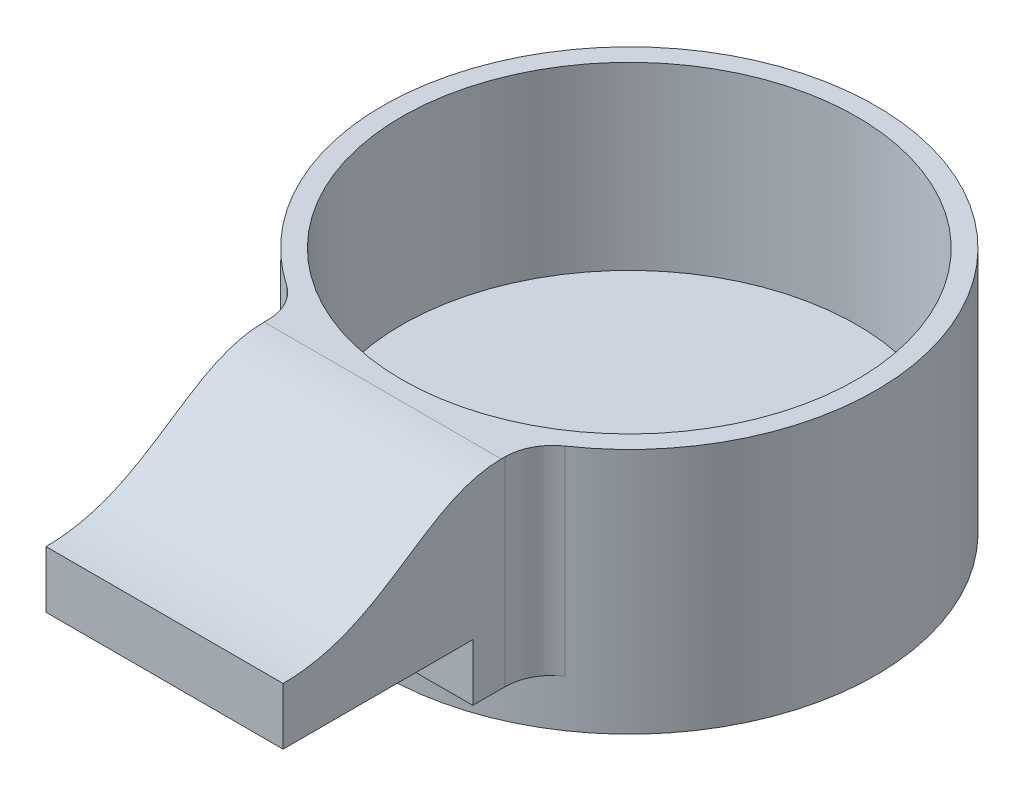
SolidWorks part; units mm, degrees
material "3.1355 (EN-AW 2024)"
ref_plane "Спереди" through (0, 0, 0) normal (0, 0, 1) x (1, 0, 0)
ref_plane "Сверху" through (0, 0, 0) normal (0, 1, 0) x (1, 0, 0)
ref_plane "Справа" through (0, 0, 0) normal (1, 0, 0) x (0, 0, -1)
sketch "Эскиз1" plane through (0, 0, 0) normal (0, 1, 0) x (1, 0, 0)
  circle A0 centre (0, 0) radius 26
  dimension "D1" = 52
extrude "Бобышка-Вытянуть1" add sketch "Эскиз1" along normal blind 2
sketch "Эскиз2" plane through (0, 2, 0) normal (0, 1, 0) x (1, 0, 0)
  circle A0 centre (0, 0) radius 26 construction
  circle A1 centre (0, 0) radius 26
  circle A2 centre (0, 0) radius 24
  dimension "D1" = 48
extrude "Бобышка-Вытянуть2" add sketch "Эскиз2" along normal blind 19
sketch "Эскиз3" plane through (0, 21, 0) normal (0, 1, 0) x (1, 0, 0)
  line L0 (0, -26) -> (0, -49) construction
  circle A0 centre (0, 0) radius 26 construction
  dimension "D1" = 23
ref_plane "Плоскость1" through (0, 0, 49) normal (0, 0, 1) x (1, 0, 0)
sketch "Эскиз4" plane through (0, 0, 49) normal (0, 0, 1) x (1, 0, 0)
  line L0 (-26, 0) -> (26, 0) construction
  line L1 (-12.5, 12) -> (12.5, 12)
  line L2 (-12.5, 12) -> (-12.5, 0)
  line L3 (-12.5, 0) -> (12.5, 0)
  line L4 (12.5, 12) -> (12.5, 0)
  point P4 (0, 0)
  dimension "D1" = 12
  dimension "D2" = 25
extrude "Бобышка-Вытянуть3" add sketch "Эскиз4" against normal up to surface (26.202 mm away)
sketch "Эскиз5" plane through (0, 0, 0) normal (0, -1, 0) x (1, 0, 0)
  line L0 (12.5, 22.798) -> (12.5, 49) construction
  line L1 (-12.5, 49) -> (12.5, 49)
  line L2 (-12.5, 49) -> (-12.5, 29)
  line L3 (-12.5, 29) -> (12.5, 29)
  line L4 (12.5, 49) -> (12.5, 29)
  dimension "D1" = 20
extrude "Вырез-Вытянуть1" cut sketch "Эскиз5" against normal blind 6
sketch "Эскиз6" plane through (12.5, 0, 0) normal (1, 0, 0) x (0, 0, -1)
  line L0 (-20.3576, 21) -> (-31.6544, 21) construction
  line L1 (-26, 21) -> (-22.798, 21)
  line L2 (24, 21) -> (-24, 21) construction
  line L3 (-22.798, 21) -> (-22.798, 12)
  line L4 (-22.798, 12) -> (-49, 12)
  line L5 (-42.591, 12) -> (-55.4136, 12) construction
  spline S0 degree 3 poles (-49, 12) (-38.3413, 12) (-34.1299, 21) (-26, 21) knots 0 0 0 0 1 1 1 1
extrude "Бобышка-Вытянуть5" add sketch "Эскиз6" against normal up to surface (25 mm away) up to face at (-12.5, 6, 33.5993)
sketch "Эскиз7" plane through (0, 21, 0) normal (0, 1, 0) x (1, 0, 0)
  circle A0 centre (0, 0) radius 24 construction
  circle A1 centre (0, 0) radius 24
extrude "Вырез-Вытянуть2" cut sketch "Эскиз7" against normal up to surface (19 mm away) up to face at (0, 2, 24)
sketch "Эскиз8" plane through (0, 0, 0) normal (0, -1, 0) x (1, 0, 0)
  arc A0 (-12.5, 22.798) -> (12.5, 22.798) centre (0, 0) ccw construction
  arc A1 (-12.5, 22.798) -> (12.5, 22.798) centre (0, 0) ccw
  circle A2 centre (0, 0) radius 24 construction
  circle A3 centre (0, 0) radius 24
  arc A4 (-12.5, 22.798) -> (12.5, 22.798) centre (0, 0) cw
extrude "Бобышка-Вытянуть6" add sketch "Эскиз8" along normal blind 5
fillet "Скругление1" radius 5 2 edges
